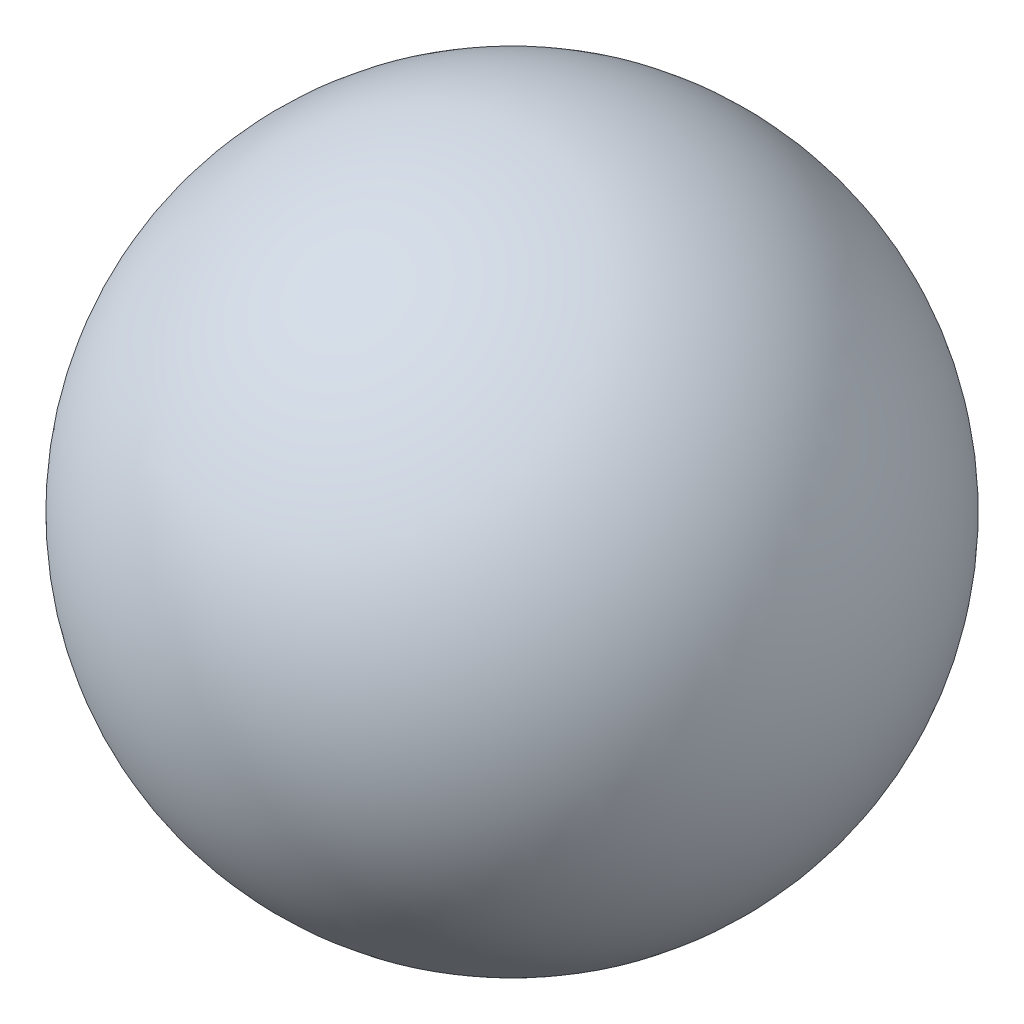
SolidWorks part; units mm, degrees
ref_plane "Front Plane" through (0, 0, 0) normal (0, 0, 1) x (1, 0, 0)
ref_plane "Top Plane" through (0, 0, 0) normal (0, 1, 0) x (1, 0, 0)
ref_plane "Right Plane" through (0, 0, 0) normal (1, 0, 0) x (0, 0, -1)
sketch "Sketch2" plane through (0, 0, 0) normal (0, 0, 1) x (1, 0, 0)
  line L0 (0, 2.921) -> (0, -2.921) construction
  line L1 (0, 2.921) -> (0, -2.921)
  arc A0 (0, -2.921) -> (0, 2.921) centre (0, 0) ccw
  dimension "D1" = 5.842
revolve "Revolve2" add sketch "Sketch2" angle 360 about L1
